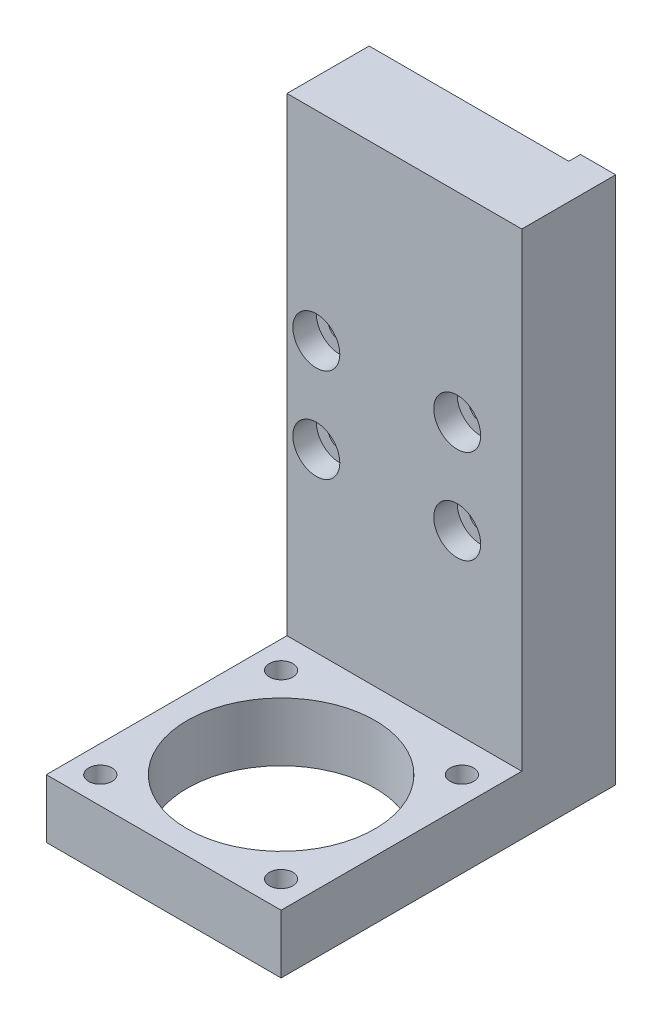
SolidWorks part; units mm, degrees
ref_plane "Front Plane" through (0, 0, 0) normal (0, 0, 1) x (1, 0, 0)
ref_plane "Top Plane" through (0, 0, 0) normal (0, 1, 0) x (1, 0, 0)
ref_plane "Right Plane" through (0, 0, 0) normal (1, 0, 0) x (0, 0, -1)
sketch "Sketch1" plane through (0, 0, 0) normal (1, 0, 0) x (0, 0, -1)
  line L0 (0, 0) -> (20.5, 0)
  line L1 (20.5, 0) -> (20.5, 40)
  line L2 (20.5, 40) -> (28.5, 40)
  line L3 (28.5, 40) -> (28.5, -5)
  line L4 (28.5, -5) -> (0, -5)
  line L5 (0, -5) -> (0, 0)
  dimension "D1" = 20.5
  dimension "D2" = 8
  dimension "D3" = 5
  dimension "D4" = 40
extrude "Boss-Extrude1" add sketch "Sketch1" along normal blind 20
sketch "Sketch3" plane through (0, 0, 0) normal (0, 1, 0) x (1, 0, 0)
  line L0 (20, 20.5) -> (20, 0) construction
  line L1 (20, 0) -> (0, 0) construction
  line L2 (0, 20.5) -> (0, 0) construction
  circle A0 centre (10, 10) radius 8
  circle A1 centre (2.3, 17.7) radius 1
  circle A2 centre (17.7, 17.7) radius 1
  circle A3 centre (17.7, 2.3) radius 1
  circle A4 centre (2.3, 2.3) radius 1
  dimension "D1" = 16
  dimension "D2" = 10
  dimension "D3" = 10
  dimension "D4" = 15.4
  dimension "D5" = 2
  dimension "D6" = 2
  dimension "D7" = 2
  dimension "D8" = 2
  dimension "D9" = 15.4
  dimension "D10" = 15.4
  dimension "D11" = 15.4
  dimension "D12" = 2.3
  dimension "D13" = 2.3
  dimension "D14" = 2.3
  dimension "D15" = 2.3
  dimension "D16" = 2.3
  dimension "D17" = 2.3
extrude "Cut-Extrude1" cut sketch "Sketch3" against normal blind 10
sketch "Sketch4" plane through (0, 0, -20.5) normal (0, 0, 1) x (1, 0, 0)
  line L0 (0, 40) -> (0, 0) construction
  line L1 (20, 0) -> (0, 0) construction
  circle A0 centre (2.5, 15) radius 1
  circle A1 centre (2.5, 23) radius 1
  circle A2 centre (14.5, 23) radius 1
  circle A3 centre (14.5, 15) radius 1
  dimension "D1" = 2
  dimension "D2" = 2
  dimension "D3" = 2
  dimension "D4" = 2
  dimension "D5" = 2.5
  dimension "D6" = 2.5
  dimension "D7" = 12
  dimension "D8" = 12
  dimension "D9" = 8
  dimension "D10" = 8
  dimension "D11" = 0
  dimension "D12" = 15
extrude "Cut-Extrude2" cut sketch "Sketch4" against normal blind 10
sketch "Sketch5" plane through (0, 0, -20.5) normal (0, 0, 1) x (1, 0, 0)
  circle A0 centre (2.5, 23) radius 2
  circle A1 centre (2.5, 15) radius 2
  circle A2 centre (14.5, 15) radius 2
  circle A3 centre (14.5, 23) radius 2
  dimension "D1" = 4
  dimension "D2" = 4
  dimension "D3" = 4
  dimension "D4" = 4
extrude "Cut-Extrude3" cut sketch "Sketch5" against normal blind 2
sketch "Sketch6" plane through (0, 40, 0) normal (0, 1, 0) x (1, 0, 0)
  line L1 (0, 28.5) -> (17, 28.5)
  line L2 (0, 28.5) -> (0, 27.5)
  line L3 (0, 27.5) -> (17, 27.5)
  line L4 (17, 28.5) -> (17, 27.5)
  dimension "D1" = 17
  dimension "D2" = 1
extrude "Cut-Extrude4" cut sketch "Sketch6" against normal blind 65
